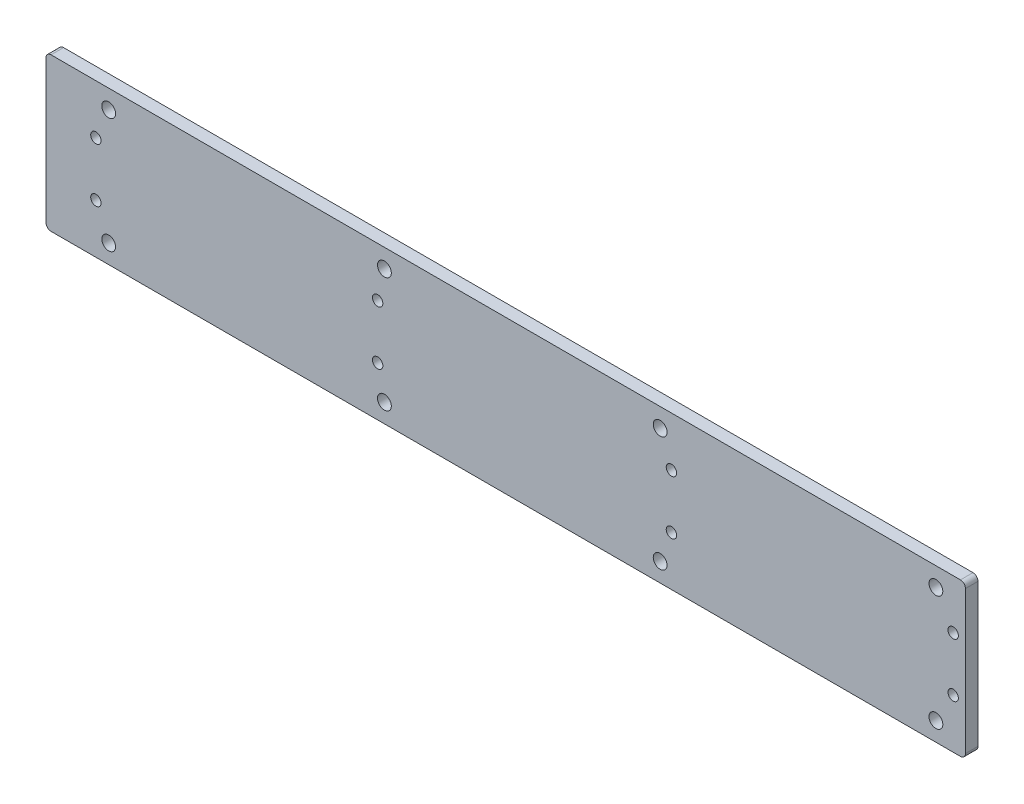
SolidWorks part; units mm, degrees
ref_plane "Alzado" through (0, 0, 0) normal (0, 0, 1) x (1, 0, 0)
ref_plane "Planta" through (0, 0, 0) normal (0, 1, 0) x (1, 0, 0)
ref_plane "Vista lateral" through (0, 0, 0) normal (1, 0, 0) x (0, 0, -1)
sketch "Croquis1" plane through (0, 0, 0) normal (0, 0, 1) x (1, 0, 0)
  line L1 (-8.795, -2.0974) -> (8.795, -2.0974)
  line L2 (-8.795, -2.0974) -> (-8.795, 2.0974)
  line L3 (-8.795, 2.0974) -> (8.795, 2.0974)
  line L4 (8.795, -2.0974) -> (8.795, 2.0974)
  line L5 (-8.795, -2.0974) -> (8.795, 2.0974) construction
  line L6 (-8.795, 2.0974) -> (8.795, -2.0974) construction
  point P0 (0, 0)
  dimension "D1" = 17.59
sketch "Croquis2" plane through (0, 0, 0) normal (0, 0, 1) x (1, 0, 0)
  line L0 (-242.443, -38.735) -> (-242.443, 38.735)
  line L1 (-223.393, -19.685) -> (223.393, -19.685) construction
  line L2 (-223.393, -19.685) -> (-223.393, 19.685) construction
  line L3 (-223.393, 19.685) -> (223.393, 19.685) construction
  line L4 (223.393, -19.685) -> (223.393, 19.685)
  line L5 (-223.393, -19.685) -> (223.393, 19.685) construction
  line L6 (-223.393, 19.685) -> (223.393, -19.685) construction
  line L7 (-242.443, 38.735) -> (223.393, 38.735)
  line L9 (-242.443, -38.735) -> (223.393, -38.735)
  line L10 (223.393, 19.685) -> (223.393, 38.735)
  line L11 (223.393, -19.685) -> (223.393, -38.735)
  line L12 (-242.443, 38.735) -> (242.443, 38.735) construction
  line L13 (242.443, -38.735) -> (242.443, 38.735) construction
  line L14 (-242.443, -38.735) -> (242.443, -38.735) construction
  point P0 (0, 0)
  dimension "D1" = 446.786
  dimension "D2" = 39.37
  dimension "D4" = 19.05
  dimension "D3" = 19.05
extrude "Saliente-Extruir1" add sketch "Croquis2" along normal blind 6.35
sketch "Croquis3" [suppressed] plane through (0, 0, 6.35) normal (0, 0, 1) x (1, 0, 0)
  line L0 (223.393, -38.735) -> (223.393, 38.735) construction
  line L1 (223.393, -19.685) -> (-223.393, -19.685)
  line L2 (223.393, -19.685) -> (223.393, 19.685)
  line L3 (223.393, 19.685) -> (-223.393, 19.685)
  line L4 (-223.393, -19.685) -> (-223.393, 19.685)
  line L5 (0, 0) -> (223.393, 0) construction
  line L6 (-242.443, 38.735) -> (-242.443, -38.735) construction
  line L7 (-242.443, -38.735) -> (223.393, -38.735) construction
  dimension "D1" = 19.05
  dimension "D2" = 446.786
  dimension "D3" = 19.05
  dimension "D4" = 39.37
extrude "Cortar-Extruir1" [suppressed] cut sketch "Croquis3" against normal through all
sketch "Croquis4" plane through (0, 0, 6.35) normal (0, 0, 1) x (1, 0, 0)
  line L0 (-9.525, 38.735) -> (-9.525, -38.735) construction
  line L1 (223.393, 38.735) -> (-242.443, 38.735) construction
  line L2 (-242.443, -38.735) -> (223.393, -38.735) construction
  line L3 (-217.17, 38.735) -> (-217.17, -38.735) construction
  line L4 (-242.443, 38.735) -> (-242.443, -38.735) construction
  line L5 (-242.443, 0) -> (223.393, 0) construction
  line L6 (223.393, -38.735) -> (223.393, 38.735) construction
  line L7 (-217.17, 16.3115) -> (-217.17, 11.049) construction
  line L8 (-217.17, -11.049) -> (-217.17, -16.3115) construction
  circle A0 centre (-217.17, 13.6802) radius 2.6312
  circle A1 centre (-217.17, -13.6802) radius 2.6312
  circle A2 centre (217.17, -13.6802) radius 2.6312
  circle A3 centre (217.17, 13.6802) radius 2.6312
  circle A4 centre (-74.422, 13.6802) radius 2.6313
  circle A5 centre (-74.422, -13.6802) radius 2.6313
  circle A6 centre (74.422, 13.6802) radius 2.6313
  circle A7 centre (74.422, -13.6802) radius 2.6313
  point P24 (-9.525, 0)
  dimension "D2" = 5.2625
  dimension "D1" = 25.273
  dimension "D3" = 22.098
  dimension "D4" = 142.748
  dimension "D5" = 142.748
  dimension "D6" = 148.844
  dimension "D7" = 6.223
  dimension "D8" = 27.3605
  dimension "D9" = 27.3605
extrude "Cortar-Extruir2" cut sketch "Croquis4" against normal through all
sketch "Croquis5" plane through (0, 0, 6.35) normal (0, 0, 1) x (1, 0, 0)
  line L0 (223.393, 19.685) -> (-223.393, 19.685) construction
  line L1 (223.393, -38.735) -> (223.393, 38.735) construction
  line L2 (-223.393, 19.685) -> (-223.393, -19.685) construction
  line L3 (-223.393, -19.685) -> (223.393, -19.685) construction
  line L4 (223.393, 38.735) -> (-242.443, 38.735) construction
  line L5 (-242.443, -38.735) -> (223.393, -38.735) construction
  line L6 (-242.443, 38.735) -> (-242.443, -38.735) construction
  line L7 (0, 38.735) -> (0, 19.685) construction
  line L8 (-223.393, 19.685) -> (-223.393, 38.735) construction
  line L9 (-223.393, 29.21) -> (223.393, 29.21) construction
  line L10 (-223.393, 0) -> (223.393, 0) construction
  circle A0 centre (-210.693, 29.21) radius 3.5
  circle A1 centre (-70.993, 29.21) radius 3.5
  circle A2 centre (68.707, 29.21) radius 3.5
  circle A3 centre (208.407, 29.21) radius 3.5
  circle A4 centre (208.407, -29.21) radius 3.5
  circle A5 centre (68.707, -29.21) radius 3.5
  circle A6 centre (-70.993, -29.21) radius 3.5
  circle A7 centre (-210.693, -29.21) radius 3.5
  dimension "D4" = 7
  dimension "D1" = 19.05
  dimension "D2" = 19.05
  dimension "D3" = 19.05
  dimension "D5" = 12.7
  dimension "D7" = 139.7
  dimension "D6" = 4
extrude "Cortar-Extruir3" cut sketch "Croquis5" against normal through all
fillet "Redondeo1" radius 2.54 4 edges at (223.393, -38.735, 3.175) (223.393, 38.735, 3.175) (-242.443, -38.735, 3.175) (-242.443, 38.735, 3.175)
fillet "Redondeo2" [suppressed] radius 2.54
